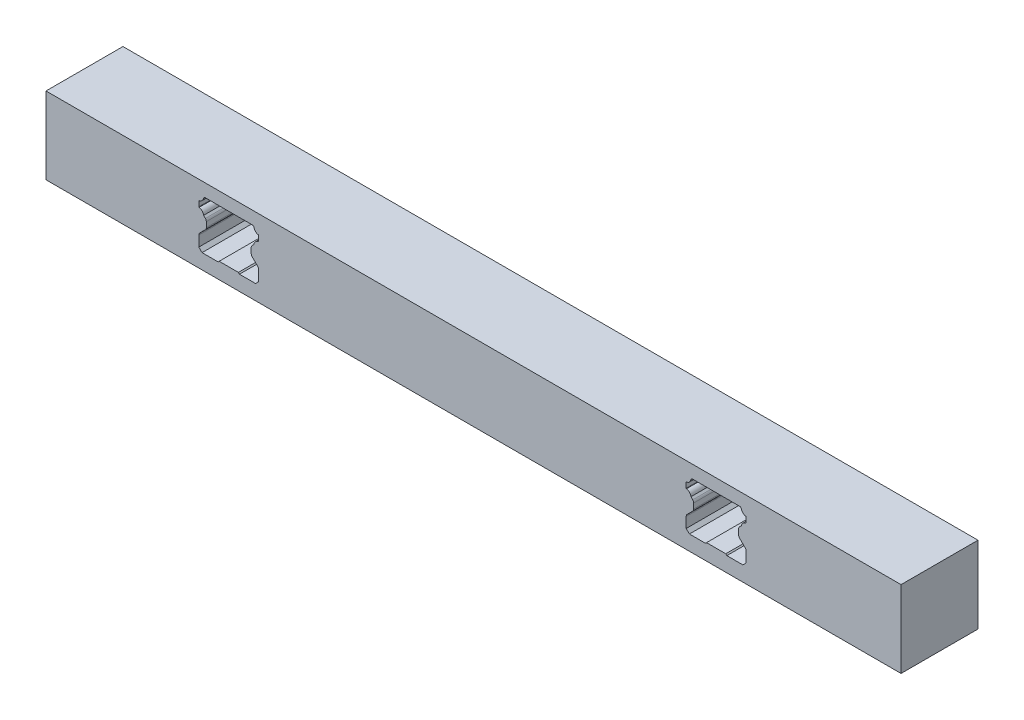
SolidWorks part; units mm, degrees
ref_plane "前视基准面" through (0, 0, 0) normal (0, 0, 1) x (1, 0, 0)
ref_plane "上视基准面" through (0, 0, 0) normal (0, 1, 0) x (1, 0, 0)
ref_plane "右视基准面" through (0, 0, 0) normal (1, 0, 0) x (0, 0, -1)
sketch "草图1" plane through (0, 0, 0) normal (0, 0, 1) x (1, 0, 0)
  line L1 (-53.1953, -6.3754) -> (346.8047, -6.3754)
  line L2 (-53.1953, -6.3754) -> (-53.1953, 29.6246)
  line L4 (346.8047, -6.3754) -> (346.8047, 29.6246)
  line L6 (-53.1953, 29.6246) -> (346.8047, 29.6246)
  line L25 (18.3047, 20.7766) -> (18.3047, 18.4726)
  line L26 (20.5465, 16.0828) -> (21.3654, 15.2639)
  line L27 (21.8047, 14.2033) -> (21.8047, 11.7457)
  line L28 (21.3654, 10.6853) -> (18.744, 8.0639)
  line L29 (18.3047, 7.0033) -> (18.3047, 2.1246)
  line L30 (18.3047, 2.1246) -> (19.8047, 0.6246)
  line L31 (19.8047, 0.6246) -> (27.3047, 0.6246)
  line L32 (27.3047, 0.6246) -> (27.8047, 1.1246)
  line L33 (27.8047, 1.1246) -> (36.8047, 1.1246)
  line L34 (36.8047, 1.1246) -> (37.3047, 0.6246)
  line L35 (37.3047, 0.6246) -> (44.8047, 0.6246)
  line L36 (44.8047, 0.6246) -> (46.3047, 2.1246)
  line L37 (46.3047, 2.1246) -> (46.3047, 7.0035)
  line L38 (45.8654, 8.0639) -> (43.244, 10.6853)
  line L39 (42.8047, 11.7459) -> (42.8047, 14.2035)
  line L40 (43.244, 15.2639) -> (44.0629, 16.0828)
  line L41 (46.3047, 18.4726) -> (46.3047, 20.7766)
  line L42 (44.0629, 23.1664) -> (43.6047, 23.6246)
  line L43 (43.6047, 23.6246) -> (21.0047, 23.6246)
  line L44 (21.0047, 23.6246) -> (20.5465, 23.1664)
  line L45 (18.3047, 20.7766) -> (18.3047, 18.4726)
  line L46 (20.5465, 16.0828) -> (21.3654, 15.2639)
  line L47 (21.8047, 14.2033) -> (21.8047, 11.7457)
  line L48 (21.3654, 10.6853) -> (18.744, 8.0639)
  line L49 (18.3047, 7.0033) -> (18.3047, 2.1246)
  line L50 (18.3047, 2.1246) -> (19.8047, 0.6246)
  line L51 (19.8047, 0.6246) -> (27.3047, 0.6246)
  line L52 (27.3047, 0.6246) -> (27.8047, 1.1246)
  line L53 (27.8047, 1.1246) -> (36.8047, 1.1246)
  line L54 (36.8047, 1.1246) -> (37.3047, 0.6246)
  line L55 (37.3047, 0.6246) -> (44.8047, 0.6246)
  line L56 (44.8047, 0.6246) -> (46.3047, 2.1246)
  line L57 (46.3047, 2.1246) -> (46.3047, 7.0035)
  line L58 (45.8654, 8.0639) -> (43.244, 10.6853)
  line L59 (42.8047, 11.7459) -> (42.8047, 14.2035)
  line L60 (43.244, 15.2639) -> (44.0629, 16.0828)
  line L61 (46.3047, 18.4726) -> (46.3047, 20.7766)
  line L62 (44.0629, 23.1664) -> (43.6047, 23.6246)
  line L63 (43.6047, 23.6246) -> (21.0047, 23.6246)
  line L64 (21.0047, 23.6246) -> (20.5465, 23.1664)
  line L65 (246.3047, 20.7766) -> (246.3047, 18.4726)
  line L66 (248.5465, 16.0828) -> (249.3654, 15.2639)
  line L67 (249.8047, 14.2033) -> (249.8047, 11.7457)
  line L68 (249.3654, 10.6853) -> (246.744, 8.0639)
  line L69 (246.3047, 7.0033) -> (246.3047, 2.1246)
  line L70 (246.3047, 2.1246) -> (247.8047, 0.6246)
  line L71 (247.8047, 0.6246) -> (255.3047, 0.6246)
  line L72 (255.3047, 0.6246) -> (255.8047, 1.1246)
  line L73 (255.8047, 1.1246) -> (264.8047, 1.1246)
  line L74 (264.8047, 1.1246) -> (265.3047, 0.6246)
  line L75 (265.3047, 0.6246) -> (272.8047, 0.6246)
  line L76 (272.8047, 0.6246) -> (274.3047, 2.1246)
  line L77 (274.3047, 2.1246) -> (274.3047, 7.0035)
  line L78 (273.8654, 8.0639) -> (271.244, 10.6853)
  line L79 (270.8047, 11.7459) -> (270.8047, 14.2035)
  line L80 (271.244, 15.2639) -> (272.0629, 16.0828)
  line L81 (274.3047, 18.4726) -> (274.3047, 20.7766)
  line L82 (272.0629, 23.1664) -> (271.6047, 23.6246)
  line L83 (271.6047, 23.6246) -> (249.0047, 23.6246)
  line L84 (249.0047, 23.6246) -> (248.5465, 23.1664)
  line L85 (246.3047, 20.7766) -> (246.3047, 18.4726)
  line L86 (248.5465, 16.0828) -> (249.3654, 15.2639)
  line L87 (249.8047, 14.2033) -> (249.8047, 11.7457)
  line L88 (249.3654, 10.6853) -> (246.744, 8.0639)
  line L89 (246.3047, 7.0033) -> (246.3047, 2.1246)
  line L90 (246.3047, 2.1246) -> (247.8047, 0.6246)
  line L91 (247.8047, 0.6246) -> (255.3047, 0.6246)
  line L92 (255.3047, 0.6246) -> (255.8047, 1.1246)
  line L93 (255.8047, 1.1246) -> (264.8047, 1.1246)
  line L94 (264.8047, 1.1246) -> (265.3047, 0.6246)
  line L95 (265.3047, 0.6246) -> (272.8047, 0.6246)
  line L96 (272.8047, 0.6246) -> (274.3047, 2.1246)
  line L97 (274.3047, 2.1246) -> (274.3047, 7.0035)
  line L98 (273.8654, 8.0639) -> (271.244, 10.6853)
  line L99 (270.8047, 11.7459) -> (270.8047, 14.2035)
  line L100 (271.244, 15.2639) -> (272.0629, 16.0828)
  line L101 (274.3047, 18.4726) -> (274.3047, 20.7766)
  line L102 (272.0629, 23.1664) -> (271.6047, 23.6246)
  line L103 (271.6047, 23.6246) -> (249.0047, 23.6246)
  line L104 (249.0047, 23.6246) -> (248.5465, 23.1664)
  arc A18 (18.4121, 21.0066) -> (18.3047, 20.7766) centre (18.6047, 20.7766) ccw
  arc A19 (18.3047, 18.4726) -> (18.4121, 18.2426) centre (18.6047, 18.4726) ccw
  arc A20 (20.5265, 16.1048) -> (18.4121, 18.2426) centre (18.0492, 15.7691) ccw
  arc A21 (20.5265, 16.1048) -> (20.5465, 16.0828) centre (20.7586, 16.2949) ccw
  arc A22 (21.8047, 14.2033) -> (21.3654, 15.2639) centre (20.3047, 14.2033) ccw
  arc A23 (21.3654, 10.6853) -> (21.8047, 11.7457) centre (20.3047, 11.7459) ccw
  arc A24 (18.744, 8.0639) -> (18.3047, 7.0033) centre (19.8047, 7.0033) ccw
  arc A25 (46.3047, 7.0035) -> (45.8654, 8.0639) centre (44.8047, 7.0033) ccw
  arc A26 (42.8047, 11.7459) -> (43.244, 10.6853) centre (44.3047, 11.7459) ccw
  arc A27 (43.244, 15.2639) -> (42.8047, 14.2035) centre (44.3047, 14.2033) ccw
  arc A28 (44.0629, 16.0828) -> (44.0828, 16.1048) centre (43.8508, 16.2949) ccw
  arc A29 (46.1973, 18.2426) -> (44.0828, 16.1048) centre (46.5602, 15.7691) ccw
  arc A30 (46.1973, 18.2426) -> (46.3047, 18.4726) centre (46.0047, 18.4726) ccw
  arc A31 (46.3047, 20.7766) -> (46.1973, 21.0066) centre (46.0047, 20.7766) ccw
  arc A32 (44.0828, 23.1444) -> (46.1973, 21.0066) centre (46.5602, 23.4801) ccw
  arc A33 (44.0828, 23.1444) -> (44.0629, 23.1664) centre (43.8508, 22.9543) ccw
  arc A34 (20.5465, 23.1664) -> (20.5265, 23.1444) centre (20.7586, 22.9543) ccw
  arc A35 (18.4121, 21.0066) -> (20.5265, 23.1444) centre (18.0492, 23.4801) ccw
  arc A36 (18.4121, 21.0066) -> (18.3047, 20.7766) centre (18.6047, 20.7766) ccw
  arc A37 (18.3047, 18.4726) -> (18.4121, 18.2426) centre (18.6047, 18.4726) ccw
  arc A38 (20.5265, 16.1048) -> (18.4121, 18.2426) centre (18.0492, 15.7691) ccw
  arc A39 (20.5265, 16.1048) -> (20.5465, 16.0828) centre (20.7586, 16.2949) ccw
  arc A40 (21.8047, 14.2033) -> (21.3654, 15.2639) centre (20.3047, 14.2033) ccw
  arc A41 (21.3654, 10.6853) -> (21.8047, 11.7457) centre (20.3047, 11.7459) ccw
  arc A42 (18.744, 8.0639) -> (18.3047, 7.0033) centre (19.8047, 7.0033) ccw
  arc A43 (46.3047, 7.0035) -> (45.8654, 8.0639) centre (44.8047, 7.0033) ccw
  arc A44 (42.8047, 11.7459) -> (43.244, 10.6853) centre (44.3047, 11.7459) ccw
  arc A45 (43.244, 15.2639) -> (42.8047, 14.2035) centre (44.3047, 14.2033) ccw
  arc A46 (44.0629, 16.0828) -> (44.0828, 16.1048) centre (43.8508, 16.2949) ccw
  arc A47 (46.1973, 18.2426) -> (44.0828, 16.1048) centre (46.5602, 15.7691) ccw
  arc A48 (46.1973, 18.2426) -> (46.3047, 18.4726) centre (46.0047, 18.4726) ccw
  arc A49 (46.3047, 20.7766) -> (46.1973, 21.0066) centre (46.0047, 20.7766) ccw
  arc A50 (44.0828, 23.1444) -> (46.1973, 21.0066) centre (46.5602, 23.4801) ccw
  arc A51 (44.0828, 23.1444) -> (44.0629, 23.1664) centre (43.8508, 22.9543) ccw
  arc A52 (20.5465, 23.1664) -> (20.5265, 23.1444) centre (20.7586, 22.9543) ccw
  arc A53 (18.4121, 21.0066) -> (20.5265, 23.1444) centre (18.0492, 23.4801) ccw
  arc A54 (246.4121, 21.0066) -> (246.3047, 20.7766) centre (246.6047, 20.7766) ccw
  arc A55 (246.3047, 18.4726) -> (246.4121, 18.2426) centre (246.6047, 18.4726) ccw
  arc A56 (248.5265, 16.1048) -> (246.4121, 18.2426) centre (246.0492, 15.7691) ccw
  arc A57 (248.5265, 16.1048) -> (248.5465, 16.0828) centre (248.7586, 16.2949) ccw
  arc A58 (249.8047, 14.2033) -> (249.3654, 15.2639) centre (248.3047, 14.2033) ccw
  arc A59 (249.3654, 10.6853) -> (249.8047, 11.7457) centre (248.3047, 11.7459) ccw
  arc A60 (246.744, 8.0639) -> (246.3047, 7.0033) centre (247.8047, 7.0033) ccw
  arc A61 (274.3047, 7.0035) -> (273.8654, 8.0639) centre (272.8047, 7.0033) ccw
  arc A62 (270.8047, 11.7459) -> (271.244, 10.6853) centre (272.3047, 11.7459) ccw
  arc A63 (271.244, 15.2639) -> (270.8047, 14.2035) centre (272.3047, 14.2033) ccw
  arc A64 (272.0629, 16.0828) -> (272.0828, 16.1048) centre (271.8508, 16.2949) ccw
  arc A65 (274.1973, 18.2426) -> (272.0828, 16.1048) centre (274.5602, 15.7691) ccw
  arc A66 (274.1973, 18.2426) -> (274.3047, 18.4726) centre (274.0047, 18.4726) ccw
  arc A67 (274.3047, 20.7766) -> (274.1973, 21.0066) centre (274.0047, 20.7766) ccw
  arc A68 (272.0828, 23.1444) -> (274.1973, 21.0066) centre (274.5602, 23.4801) ccw
  arc A69 (272.0828, 23.1444) -> (272.0629, 23.1664) centre (271.8508, 22.9543) ccw
  arc A70 (248.5465, 23.1664) -> (248.5265, 23.1444) centre (248.7586, 22.9543) ccw
  arc A71 (246.4121, 21.0066) -> (248.5265, 23.1444) centre (246.0492, 23.4801) ccw
  arc A72 (246.4121, 21.0066) -> (246.3047, 20.7766) centre (246.6047, 20.7766) ccw
  arc A73 (246.3047, 18.4726) -> (246.4121, 18.2426) centre (246.6047, 18.4726) ccw
  arc A74 (248.5265, 16.1048) -> (246.4121, 18.2426) centre (246.0492, 15.7691) ccw
  arc A75 (248.5265, 16.1048) -> (248.5465, 16.0828) centre (248.7586, 16.2949) ccw
  arc A76 (249.8047, 14.2033) -> (249.3654, 15.2639) centre (248.3047, 14.2033) ccw
  arc A77 (249.3654, 10.6853) -> (249.8047, 11.7457) centre (248.3047, 11.7459) ccw
  arc A78 (246.744, 8.0639) -> (246.3047, 7.0033) centre (247.8047, 7.0033) ccw
  arc A79 (274.3047, 7.0035) -> (273.8654, 8.0639) centre (272.8047, 7.0033) ccw
  arc A80 (270.8047, 11.7459) -> (271.244, 10.6853) centre (272.3047, 11.7459) ccw
  arc A81 (271.244, 15.2639) -> (270.8047, 14.2035) centre (272.3047, 14.2033) ccw
  arc A82 (272.0629, 16.0828) -> (272.0828, 16.1048) centre (271.8508, 16.2949) ccw
  arc A83 (274.1973, 18.2426) -> (272.0828, 16.1048) centre (274.5602, 15.7691) ccw
  arc A84 (274.1973, 18.2426) -> (274.3047, 18.4726) centre (274.0047, 18.4726) ccw
  arc A85 (274.3047, 20.7766) -> (274.1973, 21.0066) centre (274.0047, 20.7766) ccw
  arc A86 (272.0828, 23.1444) -> (274.1973, 21.0066) centre (274.5602, 23.4801) ccw
  arc A87 (272.0828, 23.1444) -> (272.0629, 23.1664) centre (271.8508, 22.9543) ccw
  arc A88 (248.5465, 23.1664) -> (248.5265, 23.1444) centre (248.7586, 22.9543) ccw
  arc A89 (246.4121, 21.0066) -> (248.5265, 23.1444) centre (246.0492, 23.4801) ccw
  dimension "D1" = 36
  dimension "D2" = 400
  dimension "D3" = 0
  dimension "D4" = 0
extrude "凸台-拉伸1" add sketch "草图1" along normal blind 36
